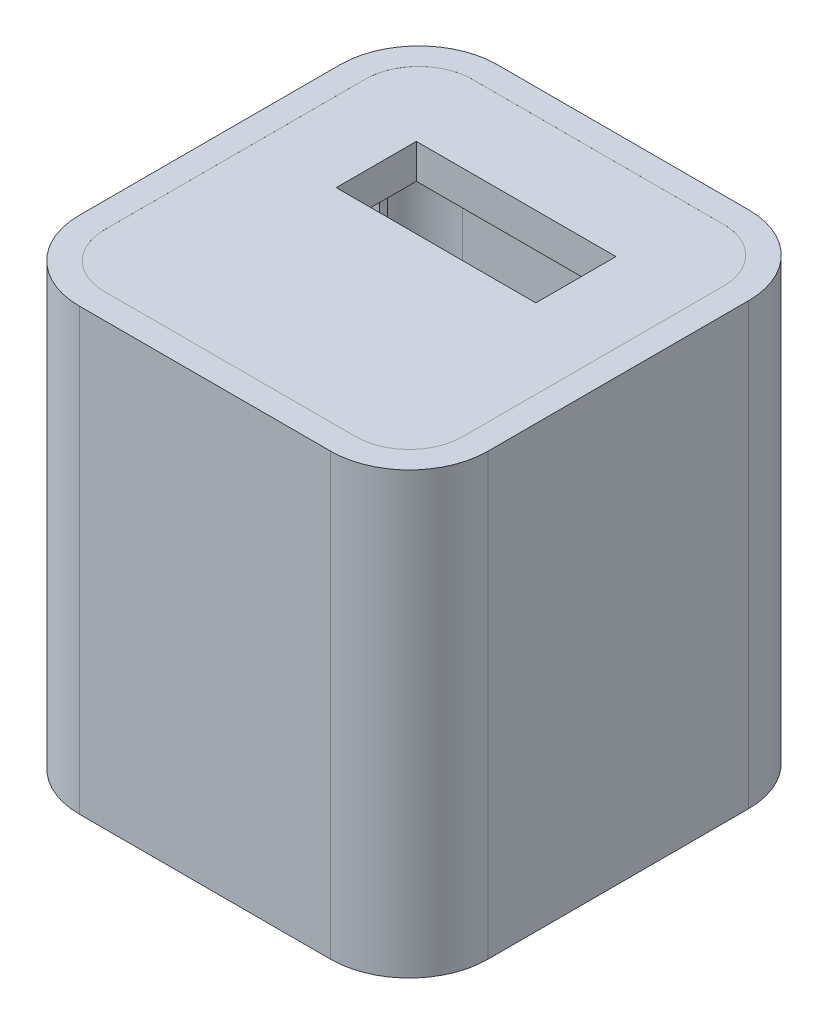
SolidWorks part; units mm, degrees
ref_plane "Plano frontal" through (0, 0, 0) normal (0, 0, 1) x (1, 0, 0)
ref_plane "Plano superior" through (0, 0, 0) normal (0, 1, 0) x (1, 0, 0)
ref_plane "Plano direito" through (0, 0, 0) normal (1, 0, 0) x (0, 0, -1)
sketch "Esboço1" plane through (0, 0, 0) normal (0, 1, 0) x (1, 0, 0)
  line L1 (-8, -13.3) -> (8, -13.3)
  line L2 (-13, -8.3) -> (-13, 8.3)
  line L3 (-8, 13.3) -> (8, 13.3)
  line L4 (13, -8.3) -> (13, 8.3)
  line L5 (-13, -13.3) -> (13, 13.3) construction
  line L6 (-13, 13.3) -> (13, -13.3) construction
  arc A0 (-8, -13.3) -> (-13, -8.3) centre (-8, -8.3) cw
  arc A1 (8, -13.3) -> (13, -8.3) centre (8, -8.3) ccw
  arc A2 (8, 13.3) -> (13, 8.3) centre (8, 8.3) cw
  arc A3 (-13, 8.3) -> (-8, 13.3) centre (-8, 8.3) cw
  point P0 (0, 0)
  dimension "D3" = 5
  dimension "D1" = 26
  dimension "D2" = 26.6
extrude "Ressalto-extrusão1" add sketch "Esboço1" along normal blind 28
shell "Casca1" thickness 2.2
sketch "Esboço2" plane through (0, 28, 0) normal (0, 1, 0) x (-1, 0, 0)
  line L0 (-8, -13.3) -> (8, -13.3) construction
  line L1 (6.35, -1.4) -> (-6.35, -1.4)
  line L2 (6.35, -1.4) -> (6.35, -6.5)
  line L3 (6.35, -6.5) -> (-6.35, -6.5)
  line L4 (-6.35, -1.4) -> (-6.35, -6.5)
  line L5 (6.35, -1.4) -> (-6.35, -6.5) construction
  line L6 (6.35, -6.5) -> (-6.35, -1.4) construction
  point P0 (0, -3.95)
  dimension "D1" = 12.7
  dimension "D2" = 0
  dimension "D3" = 5.1
  dimension "D4" = 6.8
extrude "Corte-extrusão1" cut sketch "Esboço2" against normal blind 5
sketch "Esboço3" plane through (0, 28, 0) normal (0, 1, 0) x (1, 0, 0)
  line L0 (8, 13.3) -> (-8, 13.3) construction
  line L1 (-8, -11.7) -> (8, -11.7)
  line L2 (-11.4, -8.3) -> (-11.4, 8.3)
  line L3 (-8, 11.7) -> (8, 11.7)
  line L4 (11.4, -8.3) -> (11.4, 8.3)
  line L5 (-11.4, -11.7) -> (11.4, 11.7) construction
  line L6 (-11.4, 11.7) -> (11.4, -11.7) construction
  line L8 (13, -8.3) -> (13, 8.3) construction
  arc A0 (-8, -11.7) -> (-11.4, -8.3) centre (-8, -8.3) cw
  arc A1 (8, -11.7) -> (11.4, -8.3) centre (8, -8.3) ccw
  arc A2 (8, 11.7) -> (11.4, 8.3) centre (8, 8.3) cw
  arc A3 (-11.4, 8.3) -> (-8, 11.7) centre (-8, 8.3) cw
  point P0 (0, 0)
  dimension "D3" = 3.4
  dimension "D1" = 1.6
  dimension "D2" = 1.6
extrude "Corte-extrusão2" cut sketch "Esboço3" against normal blind 0.001
sketch "Esboço4" plane through (0, 0, 0) normal (0, -1, 0) x (1, 0, 0)
  line L0 (-8, 13.3) -> (8, 13.3) construction
  line L1 (-8, -11.7) -> (8, -11.7)
  line L2 (-11.4, -8.3) -> (-11.4, 8.3)
  line L3 (-8, 11.7) -> (8, 11.7)
  line L4 (11.4, -8.3) -> (11.4, 8.3)
  line L5 (-11.4, -11.7) -> (11.4, 11.7) construction
  line L6 (-11.4, 11.7) -> (11.4, -11.7) construction
  line L7 (13, 8.3) -> (13, -8.3) construction
  arc A0 (-8, -11.7) -> (-11.4, -8.3) centre (-8, -8.3) cw
  arc A1 (8, -11.7) -> (11.4, -8.3) centre (8, -8.3) ccw
  arc A2 (8, 11.7) -> (11.4, 8.3) centre (8, 8.3) cw
  arc A3 (-11.4, 8.3) -> (-8, 11.7) centre (-8, 8.3) cw
  point P0 (0, 0)
  dimension "D3" = 3.4
  dimension "D1" = 1.6
  dimension "D2" = 1.6
extrude "Corte-extrusão3" cut sketch "Esboço4" against normal blind 2
sketch "Esboço5" plane through (0, 25.8, 0) normal (0, -1, 0) x (1, 0, 0)
  line L0 (10.8, 8.3) -> (10.8, -8.3) construction
  line L1 (10.8, -7.8) -> (9.5, -7.8)
  line L2 (10.8, -7.8) -> (10.8, -7.3)
  line L3 (10.8, -7.3) -> (9.5, -7.3)
  line L4 (9.5, -7.8) -> (9.5, -7.3)
  line L5 (8, -13.3) -> (-8, -13.3) construction
  dimension "D1" = 6
  dimension "D2" = 1.3
  dimension "D3" = 0.5
extrude "Ressalto-extrusão2" add sketch "Esboço5" along normal blind 18.3
mirror "Espelhar1" about plane through (0, 0, 0) normal (1, 0, 0) of "Ressalto-extrusão2"
